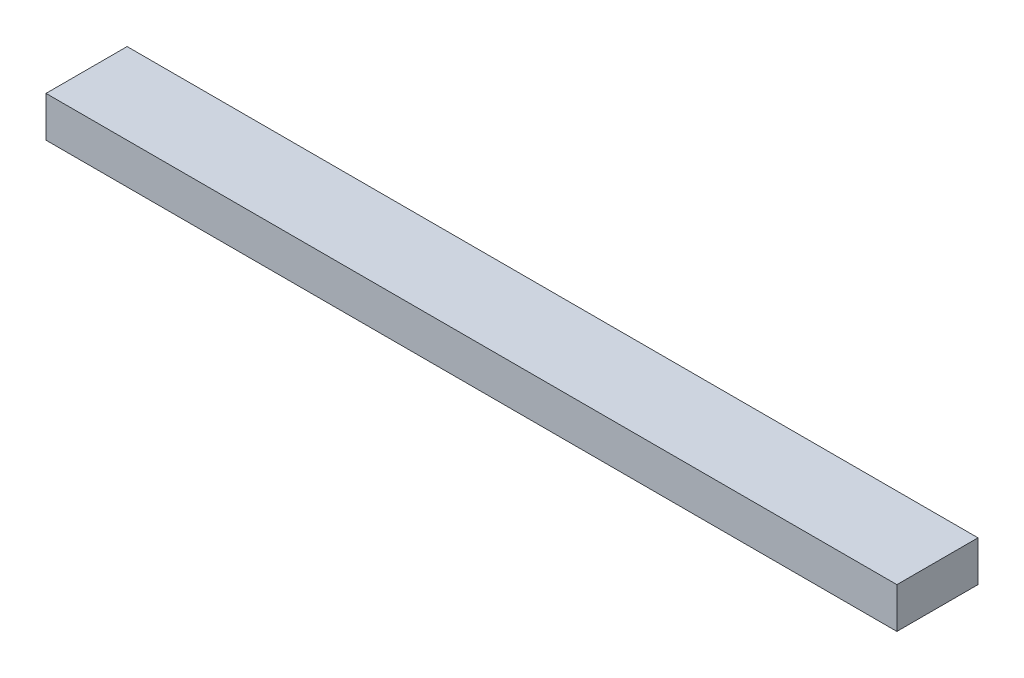
SolidWorks part; units mm, degrees
ref_plane "前视基准面" through (0, 0, 0) normal (0, 0, 1) x (1, 0, 0)
ref_plane "上视基准面" through (0, 0, 0) normal (0, 1, 0) x (1, 0, 0)
ref_plane "右视基准面" through (0, 0, 0) normal (1, 0, 0) x (0, 0, -1)
sketch "草图1" plane through (0, 0, 0) normal (0, 1, 0) x (1, 0, 0)
  line L0 (0, 0) -> (104.91, 0)
  line L1 (104.91, 0) -> (104.91, -10)
  line L2 (104.91, -10) -> (0, -10)
  line L3 (0, -10) -> (0, 0)
extrude "凸台-拉伸1" add sketch "草图1" along normal blind 5
